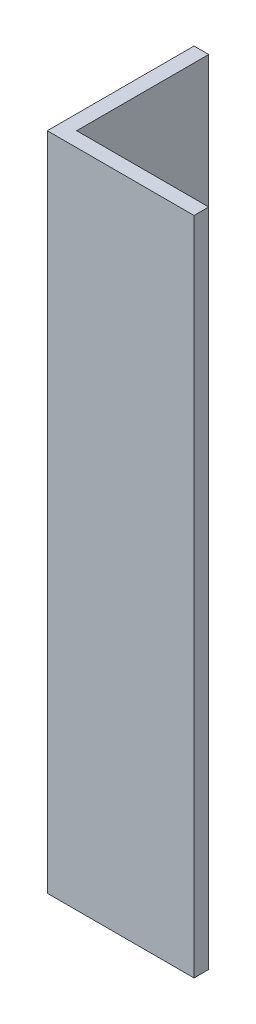
SolidWorks part; units mm, degrees
material "1060 Alloy"
ref_plane "Front Plane" through (0, 0, 0) normal (0, 0, 1) x (1, 0, 0)
ref_plane "Top Plane" through (0, 0, 0) normal (0, 1, 0) x (1, 0, 0)
ref_plane "Right Plane" through (0, 0, 0) normal (1, 0, 0) x (0, 0, -1)
sketch "Sketch1" plane through (0, 0, 0) normal (0, 1, 0) x (1, 0, 0)
  line L1 (0, 0) -> (20, 0)
  line L2 (0, 0) -> (0, 20)
  line L3 (0, 20) -> (2, 20)
  line L4 (20, 0) -> (20, 2)
  line L7 (20, 2) -> (2, 2)
  line L8 (2, 20) -> (2, 2)
  dimension "D1" = 20
  dimension "D2" = 20
  dimension "D3" = 2
  dimension "D4" = 2
extrude "Boss-Extrude1" add sketch "Sketch1" along normal blind 90
